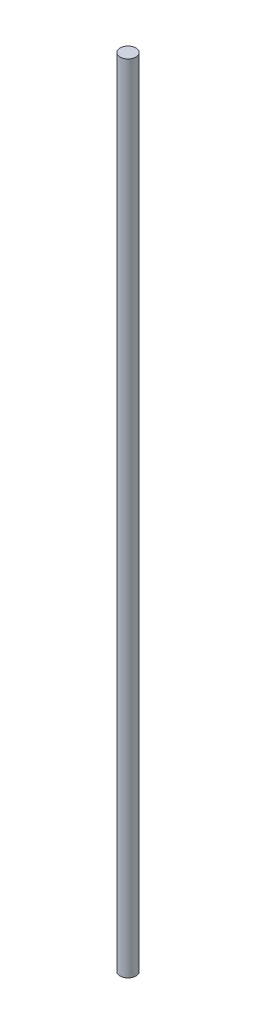
SolidWorks part; units mm, degrees
ref_plane "前视基准面" through (0, 0, 0) normal (0, 0, 1) x (1, 0, 0)
ref_plane "上视基准面" through (0, 0, 0) normal (0, 1, 0) x (1, 0, 0)
ref_plane "右视基准面" through (0, 0, 0) normal (1, 0, 0) x (0, 0, -1)
other "Configuration Table"
sketch "草图1" plane through (0, 0, 0) normal (0, 1, 0) x (1, 0, 0)
  circle A0 centre (0, 0) radius 4
  dimension "D1" = 8
extrude "凸台-拉伸1" add sketch "草图1" along normal blind 400
